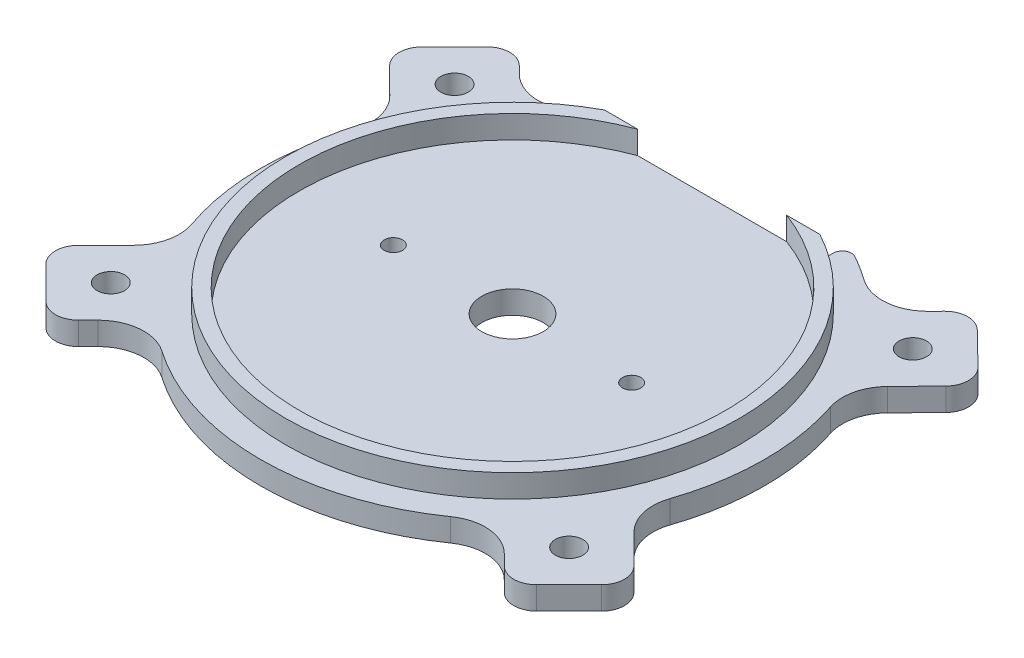
SolidWorks part; units mm, degrees
ref_plane "前视基准面" through (0, 0, 0) normal (0, 0, 1) x (1, 0, 0)
ref_plane "上视基准面" through (0, 0, 0) normal (0, 1, 0) x (1, 0, 0)
ref_plane "右视基准面" through (0, 0, 0) normal (1, 0, 0) x (0, 0, -1)
other "Configuration Table"
sketch "草图1" plane through (0, 0, 0) normal (0, 1, 0) x (1, 0, 0)
  circle A0 centre (0, 0) radius 55
  dimension "D1" = 110
extrude "凸台-拉伸1" add sketch "草图1" along normal blind 5
sketch "草图5" plane through (0, 5, 0) normal (0, 1, 0) x (1, 0, 0)
  line L0 (0, 0) -> (0, 49.5) construction
  line L1 (-23.5, 43.566) -> (23.5, 43.566)
  line L2 (-23.5, 43.566) -> (-23.5, 55.8089)
  line L3 (-23.5, 55.8089) -> (23.5, 55.8089)
  line L4 (23.5, 55.8089) -> (23.5, 43.566)
  dimension "D1" = 47
extrude "切除-拉伸2" cut sketch "草图5" against normal blind 30
fillet "圆角4" radius 2 1 edges at (-23.5, 2.5, -49.7268)
fillet "圆角5" radius 2 1 edges at (23.5, 2.5, -49.7268)
sketch "草图10" plane through (0, 3, 0) normal (0, 1, 0) x (1, 0, 0)
  line L0 (-49.7204, 37.0712) -> (62.5452, 37.0712) construction
  line L1 (-49.7204, 37.0712) -> (-49.7204, -35.3765) construction
  line L2 (-49.7204, -37.9288) -> (73.1761, -37.9288) construction
  circle A0 centre (-49.7204, 37.0712) radius 3
  circle A1 centre (50.2796, 37.0712) radius 3
  circle A2 centre (-49.7204, -37.9288) radius 3
  circle A3 centre (50.2796, -37.9288) radius 3
  dimension "D1" = 6
  dimension "D2" = 6
  dimension "D4" = 6
  dimension "D6" = 6
  dimension "D3" = 100
  dimension "D5" = 75
  dimension "D7" = 100
sketch "草图14" plane through (0, 3, 0) normal (0, 1, 0) x (1, 0, 0)
  line L0 (-49.8986, 23.1329) -> (-63.8625, 37.0448)
  line L1 (-63.8625, 37.0448) -> (-49.7468, 51.2133)
  line L2 (-49.7468, 51.2133) -> (-38.1286, 39.6385)
  line L3 (49.8119, -23.319) -> (64.4217, -37.9288)
  line L4 (-49.6324, -23.6986) -> (-63.8626, -37.9288)
  line L5 (-63.8626, -37.9288) -> (-49.7204, -52.0709)
  line L6 (-49.7204, -52.0709) -> (-37.6979, -40.0484)
  line L7 (38.4757, 39.3016) -> (50.1189, 51.2124)
  line L8 (50.1189, 51.2124) -> (64.4208, 37.2319)
  line L9 (64.4208, 37.2319) -> (50.1345, 22.6171)
  line L10 (64.4217, -37.9288) -> (50.2796, -52.0709)
  line L11 (50.2796, -52.0709) -> (37.9849, -39.7762)
  arc A0 (-26.4623, 48.2156) -> (26.4623, 48.2156) centre (0, 0) ccw construction
  arc A1 (-49.6324, -23.6986) -> (-37.6979, -40.0484) centre (0, 0) ccw
  arc A2 (-49.8986, 23.1329) -> (-38.1286, 39.6385) centre (0, 0) cw
  arc A3 (38.4757, 39.3016) -> (50.1345, 22.6171) centre (0, 0) cw
  arc A4 (49.8119, -23.319) -> (37.9849, -39.7762) centre (0, 0) cw
  dimension "D1" = 10
  dimension "D2" = 10
  dimension "D3" = 10
  dimension "D4" = 10
  dimension "D5" = 10
  dimension "D6" = 10
  dimension "D7" = 10
  dimension "D8" = 10
  dimension "D9" = 10
  dimension "D10" = 10
  dimension "D11" = 10
  dimension "D12" = 10
extrude "凸台-拉伸3" add sketch "草图14" against normal up to surface and the other way up to surface up to face at (0, 0, -29.1602) other way up to face at (0, 5, -29.1602)
fillet "圆角7" radius 10 8 edges at (-49.6324, 2.5, 23.6986) (-37.6979, 2.5, 40.0484) (37.9849, 2.5, 39.7762) (49.8119, 2.5, 23.319) (50.1345, 2.5, -22.6171) (38.4757, 2.5, -39.3016) (-38.1286, 2.5, -39.6385) (-49.8986, 2.5, -23.1329)
fillet "圆角8" radius 5 8 edges at (-49.7468, 2.5, -51.2133) (-63.8625, 2.5, -37.0448) (-63.8626, 2.5, 37.9288) (-49.7204, 2.5, 52.0709) (50.2796, 2.5, 52.0709) (64.4217, 2.5, 37.9288) (64.4208, 2.5, -37.2319) (50.1189, 2.5, -51.2124)
extrude "切除-拉伸5" cut sketch "草图10" against normal mid plane 10
sketch "草图15" plane through (0, 5, 0) normal (0, 1, 0) x (1, 0, 0)
  circle A0 centre (0, 0) radius 6.7
  dimension "D1" = 13.4
extrude "切除-拉伸6" cut sketch "草图15" against normal blind 10
sketch "草图16" plane through (0, 5, 0) normal (0, 1, 0) x (1, 0, 0)
  line L0 (0, 0) -> (-35.2321, 0) construction
  circle A0 centre (-26, 0) radius 2
  circle A1 centre (26, 0) radius 2
  dimension "D1" = 4
  dimension "D2" = 4
  dimension "D3" = 52
  dimension "D4" = 26
extrude "切除-拉伸7" cut sketch "草图16" against normal blind 10
sketch "草图17" plane through (0, 5, 0) normal (0, 1, 0) x (1, 0, 0)
  line L0 (-23.5, 43.566) -> (23.5, 43.566) construction
  line L1 (-23.5, 43.566) -> (-16.2558, 43.566)
  line L2 (16.2558, 43.566) -> (23.5, 43.566)
  arc A0 (23.5, 43.566) -> (-23.5, 43.566) centre (0, 0) cw
  arc A1 (-16.2558, 43.566) -> (16.2558, 43.566) centre (0, 0) ccw
extrude "凸台-拉伸4" add sketch "草图17" along normal blind 5
